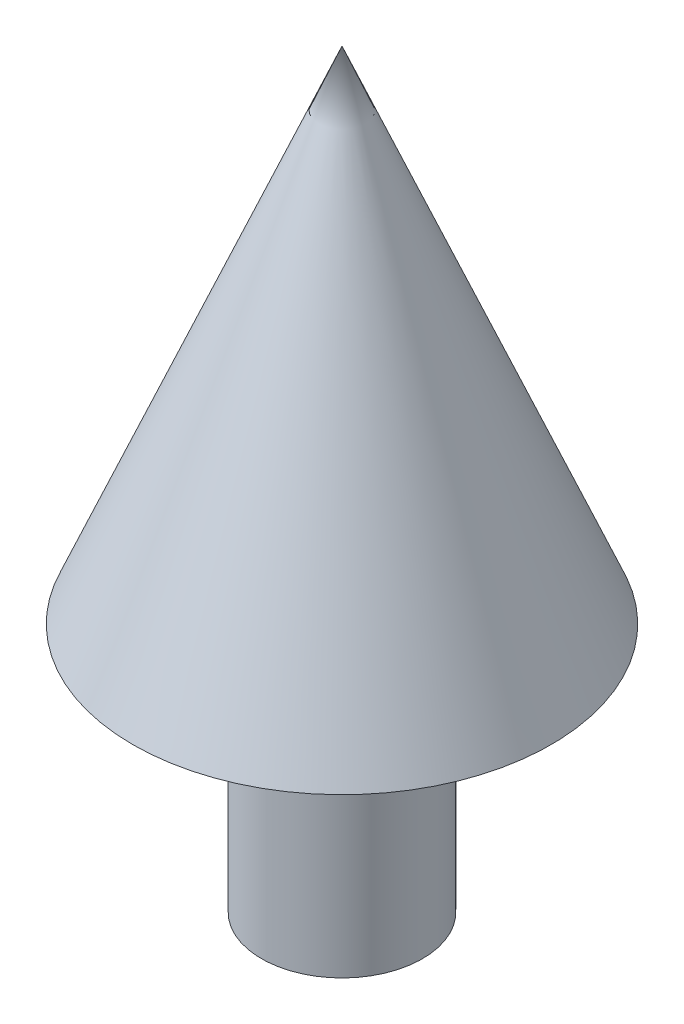
SolidWorks part; units mm, degrees
ref_plane "Front" through (0, 0, 0) normal (0, 0, 1) x (1, 0, 0)
ref_plane "Top" through (0, 0, 0) normal (0, 1, 0) x (1, 0, 0)
ref_plane "Right" through (0, 0, 0) normal (1, 0, 0) x (0, 0, -1)
sketch "Sketch1" plane through (0, 0, 0) normal (0, 0, 1) x (1, 0, 0)
  line L0 (0, 0) -> (0, 914.4)
  line L1 (0, 914.4) -> (254.9022, 304.3293)
  line L2 (254.9022, 304.3293) -> (98.148, 365.0539)
  line L3 (98.148, 365.0539) -> (98.148, 0)
  line L4 (98.148, 0) -> (0, 0)
  dimension "D1" = 914.4
revolve "Revolve1" add sketch "Sketch1" angle 360 about L0
